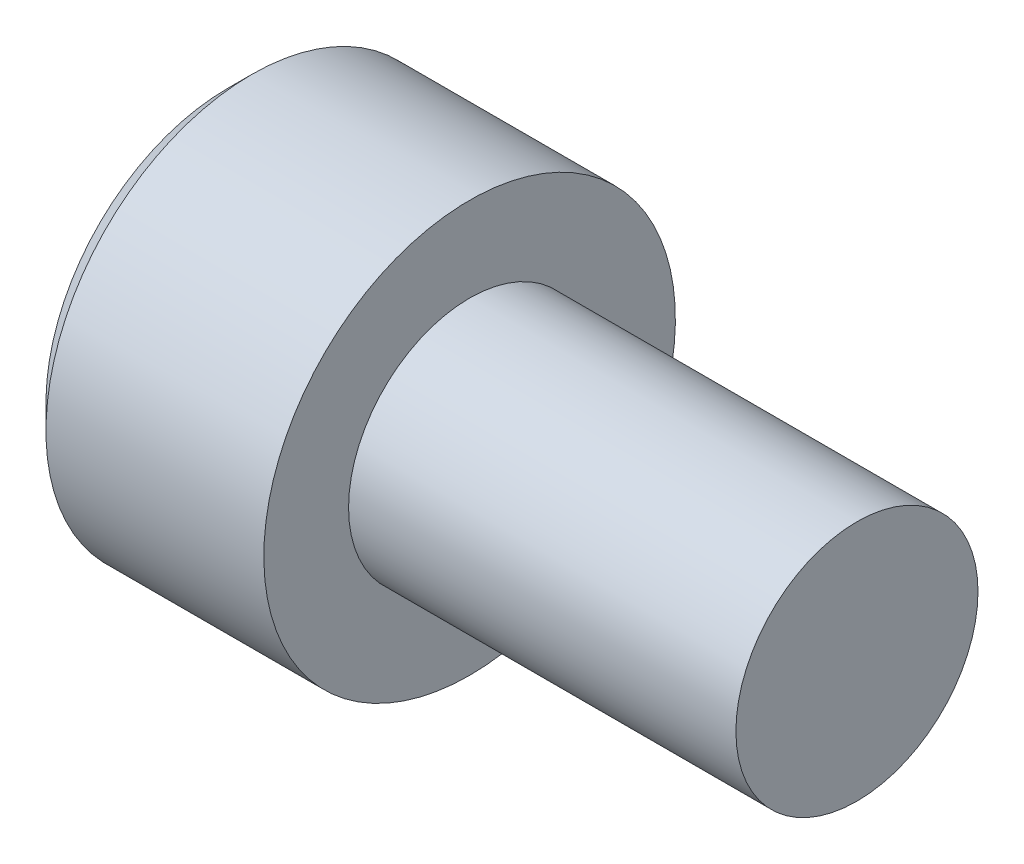
SolidWorks part; units mm, degrees
ref_plane "Front Plane" through (0, 0, 0) normal (0, 0, 1) x (1, 0, 0)
ref_plane "Top Plane" through (0, 0, 0) normal (0, 1, 0) x (1, 0, 0)
ref_plane "Right Plane" through (0, 0, 0) normal (1, 0, 0) x (0, 0, -1)
sketch "Sketch1" plane through (0, 0, 0) normal (0, 0, 1) x (1, 0, 0)
  line L0 (-5, 0) -> (8, 0) construction
  line L1 (0, 2.5) -> (8, 2.5)
  line L3 (-5, 0) -> (8, 0)
  line L4 (8, 2.5) -> (8, 0)
  line L6 (0, 2.5) -> (0, 4.25)
  line L7 (0, 4.25) -> (-5, 4.25)
  line L8 (-5, 0) -> (-5, 4.25)
  dimension "L" = 8
  dimension "M" = 5
  dimension "E" = 5
  dimension "A" = 8.5
revolve "Revolve1" add sketch "Sketch1" about L0
cosmetic thread "Thread1" parameters "L_s"=8, "ATD"=4.134
sketch "Sketch2" plane through (0, 0, 0) normal (0, 0, 1) x (1, 0, 0)
  line L0 (-5, 0) -> (-1.2983, 0) construction
  line L1 (-5, 0) -> (8, 0) construction
  line L2 (-1.2983, 0) -> (-2.5, 2)
  line L3 (-2.5, 2) -> (-5, 2)
  line L4 (-5, 0) -> (-5, 4.25) construction
  line L5 (-5, 2) -> (-5, 0)
  line L6 (-5, 0) -> (-1.2983, 0)
  dimension "MSM_1" = 2.5
  dimension "FIX_2" = 59
revolve "Cut-Revolve1" cut sketch "Sketch2" about L0
sketch "Sketch3" plane through (-5, 0, 0) normal (-1, 0, 0) x (0, 0, 1)
  line L0 (0, -4.675) -> (0, 4.675) construction
  line L1 (2, 1.1547) -> (0, 2.3094)
  line L2 (0, 2.3094) -> (-2, 1.1547)
  line L3 (-2, 1.1547) -> (-2, -1.1547)
  line L4 (-2, -1.1547) -> (0, -2.3094)
  line L5 (0, -2.3094) -> (2, -1.1547)
  line L6 (2, -1.1547) -> (2, 1.1547)
  circle A0 centre (0, 0) radius 2 construction
extrude "Cut-Extrude1" cut sketch "Sketch3" against normal blind 2.5
chamfer "Chamfer1" distance 0.5 1 edges at (-5, -4.25, 0)
